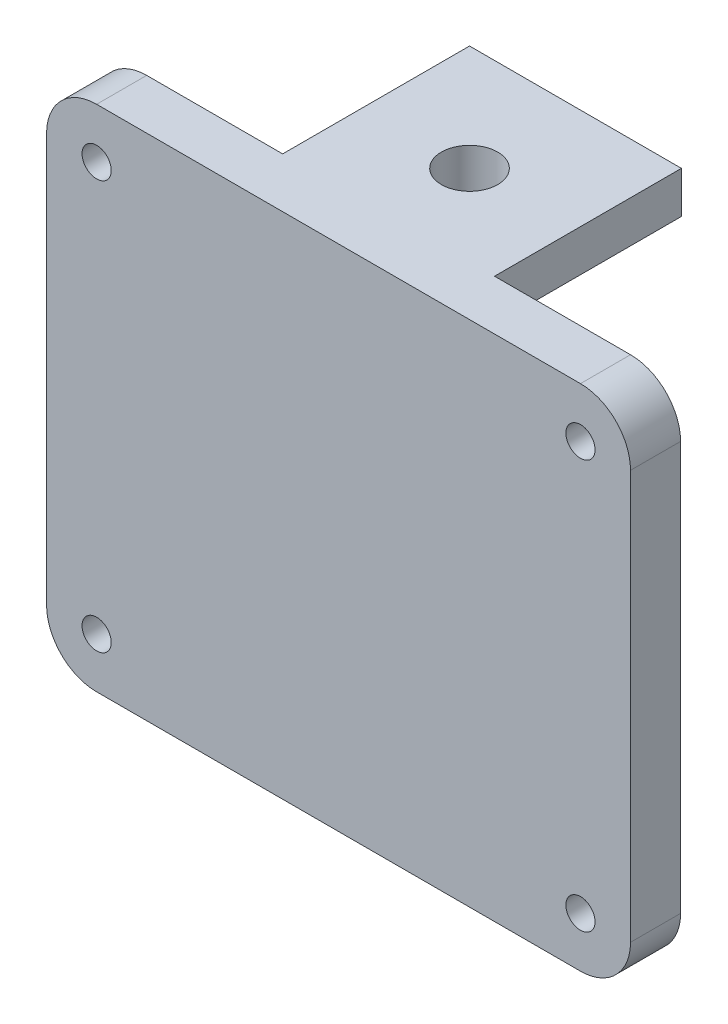
SolidWorks part; units mm, degrees
ref_plane "Front Plane" through (0, 0, 0) normal (0, 0, 1) x (1, 0, 0)
ref_plane "Top Plane" through (0, 0, 0) normal (0, 1, 0) x (1, 0, 0)
ref_plane "Right Plane" through (0, 0, 0) normal (1, 0, 0) x (0, 0, -1)
sketch "Sketch1" plane through (0, 0, 0) normal (0, 1, 0) x (1, 0, 0)
  line L1 (-12.7, 12.7) -> (12.7, 12.7)
  line L2 (-12.7, 12.7) -> (-12.7, -12.7)
  line L3 (-12.7, -12.7) -> (12.7, -12.7)
  line L4 (12.7, 12.7) -> (12.7, -12.7)
  line L5 (-12.7, 12.7) -> (12.7, -12.7) construction
  line L6 (-12.7, -12.7) -> (12.7, 12.7) construction
  point P0 (0, 0)
  dimension "D1" = 25.4
  dimension "D2" = 25.4
extrude "Boss-Extrude1" add sketch "Sketch1" along normal blind 5
hole_wizard "1/4 Clearance Hole1" positions "Sketch2" profile "Sketch3" hole size "1/4" standard "ANSI Inch" end condition through all
sketch "Sketch2" plane through (0, 5, 0) normal (0, 1, 0) x (1, 0, 0)
  point P0 (0, 0)
sketch "Sketch3" plane through (0, 5, 0) normal (1, 0, 0) x (0, 0, 1)
  line L0 (0, 0) -> (0, 5)
  line L1 (0, 5) -> (3.3782, 5)
  line L2 (3.3782, 5) -> (3.3782, 0)
  line L5 (3.3782, 0) -> (0, 0)
  line L11 (0, -6.35) -> (0, 107.95) construction
  dimension "Thru Hole Dia." = 6.7564
  dimension "Thru Hole Depth" = 5
sketch "Sketch4" plane through (0, 0, 12.7) normal (0, 0, 1) x (1, 0, 0)
  line L0 (-35, -56) -> (-35, 5)
  line L1 (-29, -50) -> (29, -50) construction
  line L2 (-29, -50) -> (-29, -1) construction
  line L3 (-29, -1) -> (29, -1) construction
  line L4 (29, -50) -> (29, -1) construction
  line L5 (-29, -50) -> (29, -1) construction
  line L6 (-29, -1) -> (29, -50) construction
  line L7 (-35, 5) -> (35, 5)
  line L8 (35, -56) -> (35, 5)
  line L9 (-35, -56) -> (35, -56)
  line L10 (-12.7, 5) -> (12.7, 5) construction
  circle A0 centre (-29, -1) radius 1.75
  circle A1 centre (29, -1) radius 1.75
  circle A2 centre (29, -50) radius 1.75
  circle A3 centre (-29, -50) radius 1.75
  point P0 (0, -25.5)
  line M9 (-12.7, 0) -> (12.7, 0)
  line M10 (12.7, 0) -> (12.7, 5)
  line M11 (12.7, 5) -> (-12.7, 5)
  line M12 (-12.7, 5) -> (-12.7, 0)
  dimension "D4" = 3.5
  dimension "D1" = 6
  dimension "D2" = 58
  dimension "D3" = 49
extrude "Boss-Extrude2" add sketch "Sketch4" against normal mid plane 6 contours L0 L9 L8 L7 A3 A2 A1 A0 M10 M9 M12 | M12 M9 M10 M11
fillet "Fillet1" radius 6 4 edges at (35, -56, 12.7) (-35, -56, 12.7) (35, 5, 12.7) (-35, 5, 12.7)
